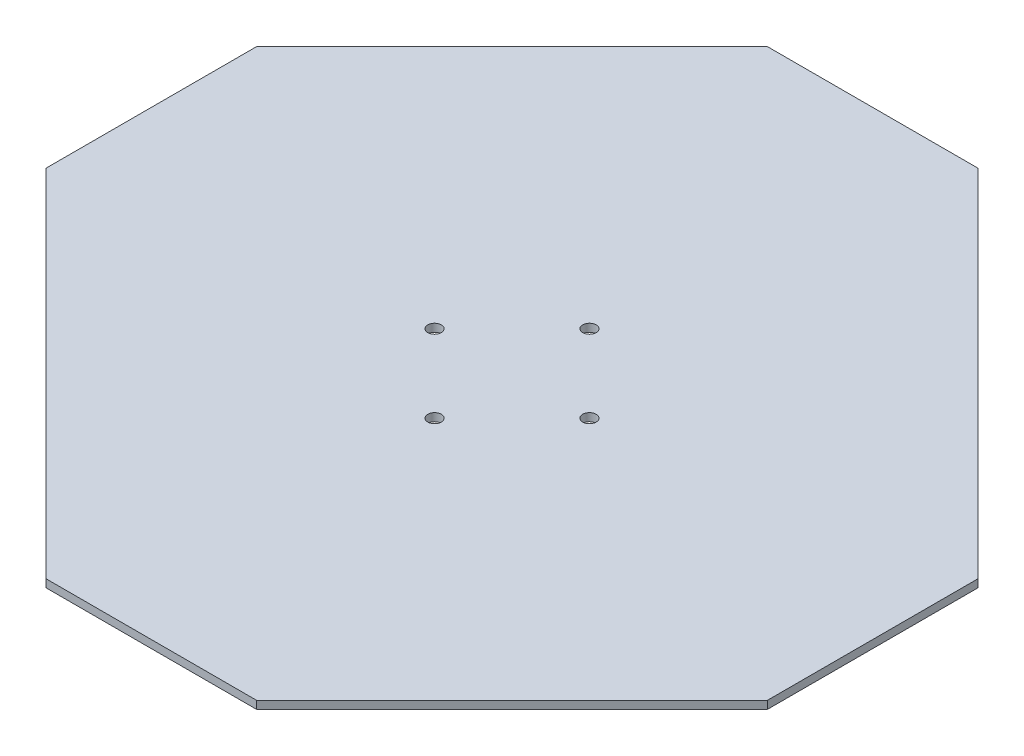
SolidWorks part; units mm, degrees
ref_plane "Front Plane" through (0, 0, 0) normal (0, 0, 1) x (1, 0, 0)
ref_plane "Top Plane" through (0, 0, 0) normal (0, 1, 0) x (1, 0, 0)
ref_plane "Right Plane" through (0, 0, 0) normal (1, 0, 0) x (0, 0, -1)
sketch "Sketch1" plane through (0, 0, 0) normal (0, 1, 0) x (1, 0, 0)
  line L0 (0, 0) -> (-88.7419, -88.7419) construction
  line L1 (68.75, -165.9772) -> (165.9772, -68.75) construction
  line L2 (165.9772, -68.75) -> (165.9772, 68.75) construction
  line L3 (165.9772, 68.75) -> (68.75, 165.9772) construction
  line L4 (68.75, 165.9772) -> (-68.75, 165.9772) construction
  line L5 (-68.75, 165.9772) -> (-165.9772, 68.75) construction
  line L6 (-165.9772, 68.75) -> (-165.9772, -68.75) construction
  line L7 (-165.9772, -68.75) -> (-68.75, -165.9772) construction
  line L8 (-68.75, -165.9772) -> (68.75, -165.9772) construction
  line L9 (117.3636, 117.3636) -> (-117.3636, -117.3636) construction
  line L10 (0, 0) -> (88.7419, 88.7419) construction
  line L11 (-88.7419, -88.7419) -> (-11.5066, -165.9772) construction
  line L12 (-11.5066, -165.9772) -> (-165.9772, -11.5066) construction
  line L13 (88.7419, 88.7419) -> (165.9772, 11.5066) construction
  line L14 (165.9772, 11.5066) -> (11.5066, 165.9772) construction
  circle A0 centre (0, 0) radius 165.9772 construction
  dimension "D1" = 137.5
sketch "Sketch3" plane through (0, 0, 0) normal (0, 1, 0) x (1, 0, 0)
  line L3 (146.9176, 30.5662) -> (11.5066, 165.9772)
  line L4 (11.5066, 165.9772) -> (-68.75, 165.9772)
  line L5 (-68.75, 165.9772) -> (-165.9772, 68.75)
  line L6 (-165.9772, 68.75) -> (-165.9772, -11.5066)
  line L7 (-165.9772, -11.5066) -> (-30.5662, -146.9176)
  line L8 (-68.75, 165.9772) -> (146.9176, -49.6904) construction
  line L9 (-165.9772, 68.75) -> (49.6904, -146.9176) construction
  line L10 (49.6904, -146.9176) -> (146.9176, -49.6904)
  line L11 (146.9176, 30.5662) -> (146.9176, -49.6904)
  line L12 (49.6904, -146.9176) -> (-30.5662, -146.9176)
extrude "Boss-Extrude2" add sketch "Sketch3" along normal blind 3
hole_wizard "13/64 (0.20313) Diameter Hole1" positions "Sketch8" profile "Sketch7" hole size "13/64" standard "ANSI Inch" end condition up to next
sketch "Sketch8" plane through (0, 0, 0) normal (0, -1, 0) x (-1, 0, 0)
  point P0 (39.0298, 9.5282)
  point P3 (9.5282, -19.9702)
  point P6 (-19.9702, 9.5314)
  point P9 (9.5314, 39.0298)
sketch "Sketch7" plane through (-39.0298, 0, -9.5282) normal (1, 0, 0) x (0, 0, -1)
  line L0 (0, 0) -> (0, 3)
  line L1 (0, 3) -> (2.5798, 3)
  line L2 (2.5798, 3) -> (2.5798, 0)
  line L5 (2.5798, 0) -> (0, 0)
  line L11 (0, -6.35) -> (0, 107.95) construction
  dimension "Thru Hole Dia." = 5.1595
  dimension "Thru Hole Depth" = 3
sketch "Sketch11" plane through (0, 0, 0) normal (0, -1, 0) x (-1, 0, 0)
  line L0 (98.2717, -79.2121) -> (-79.2121, 98.2717)
  line L1 (165.9772, -11.5066) -> (30.5662, -146.9176) construction
  line L2 (-146.9176, 30.5662) -> (-11.5066, 165.9772) construction
  line L3 (-79.2121, 98.2717) -> (9.5298, 9.5298)
  line L4 (9.5298, 9.5298) -> (36.0463, 36.0463)
